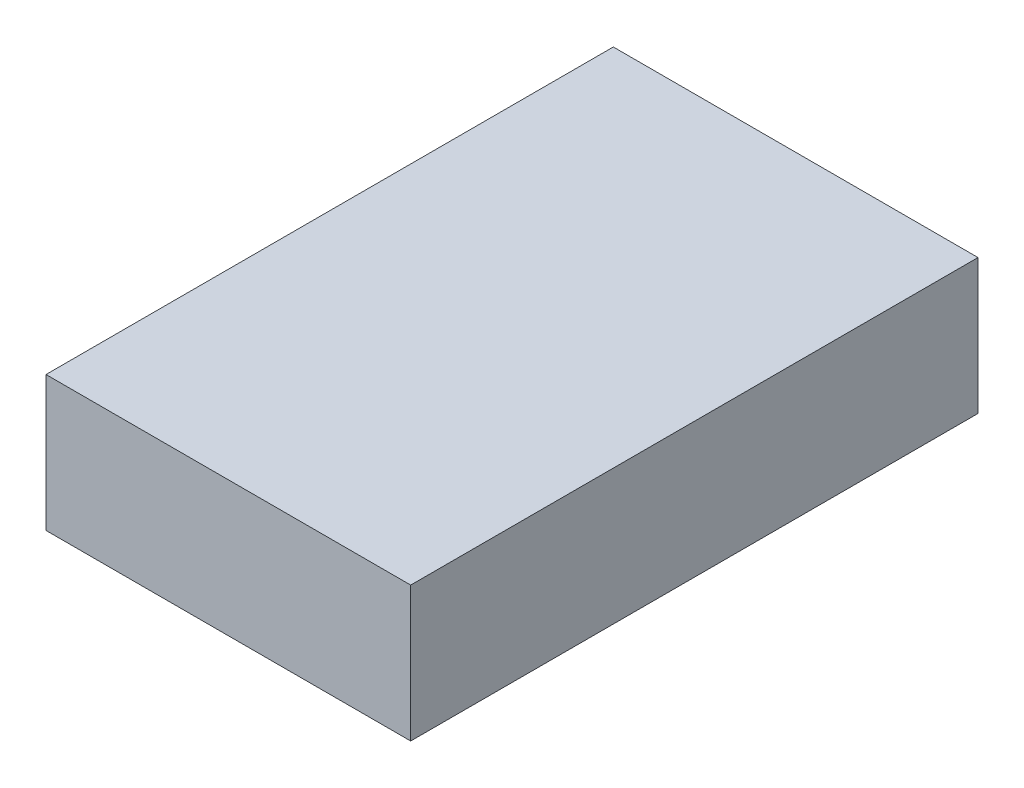
SolidWorks part; units mm, degrees
ref_plane "Front Plane" through (0, 0, 0) normal (0, 0, 1) x (1, 0, 0)
ref_plane "Top Plane" through (0, 0, 0) normal (0, 1, 0) x (1, 0, 0)
ref_plane "Right Plane" through (0, 0, 0) normal (1, 0, 0) x (0, 0, -1)
sketch "Sketch1" plane through (0, 0, 0) normal (0, 0, 1) x (1, 0, 0)
  line L1 (-67.5, -25) -> (67.5, -25)
  line L2 (-67.5, -25) -> (-67.5, 25)
  line L3 (-67.5, 25) -> (67.5, 25)
  line L4 (67.5, -25) -> (67.5, 25)
  line L5 (-67.5, -25) -> (67.5, 25) construction
  line L6 (-67.5, 25) -> (67.5, -25) construction
  point P0 (0, 0)
  dimension "D1" = 135
  dimension "D2" = 50
extrude "Boss-Extrude1" add sketch "Sketch1" along normal blind 210
